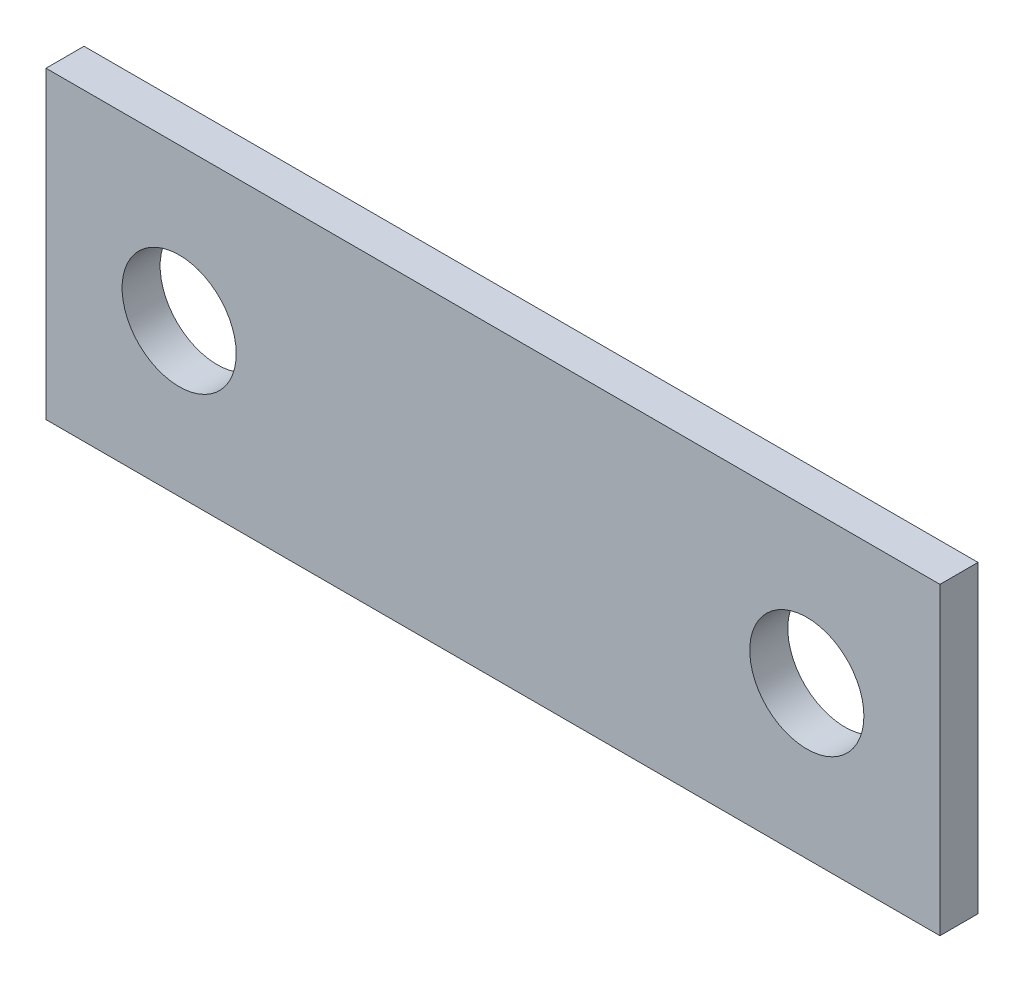
SolidWorks part; units mm, degrees
ref_plane "Front" through (0, 0, 0) normal (0, 0, 1) x (1, 0, 0)
ref_plane "Top" through (0, 0, 0) normal (0, 1, 0) x (1, 0, 0)
ref_plane "Right" through (0, 0, 0) normal (1, 0, 0) x (0, 0, -1)
sketch "Sketch1" plane through (0, 0, 0) normal (0, 0, 1) x (1, 0, 0)
  line L0 (26.1937, 0) -> (-26.1937, 0) construction
  line L1 (37.3063, -12.7) -> (-37.3062, -12.7)
  line L2 (37.3063, -12.7) -> (37.3063, 12.7)
  line L3 (37.3063, 12.7) -> (-37.3062, 12.7)
  line L4 (-37.3062, -12.7) -> (-37.3062, 12.7)
  line L5 (37.3063, -12.7) -> (-37.3062, 12.7) construction
  line L6 (37.3063, 12.7) -> (-37.3062, -12.7) construction
  circle A0 centre (-26.1937, 0) radius 4.7625
  circle A1 centre (26.1937, 0) radius 4.7625
  point P0 (0, 0)
  dimension "Hole Size" = 9.525
  dimension "Length" = 74.6125
  dimension "Width" = 25.4
  dimension "Center to Center " = 52.3875
extrude "Boss-Extrude1" add sketch "Sketch1" along normal blind 3.175
